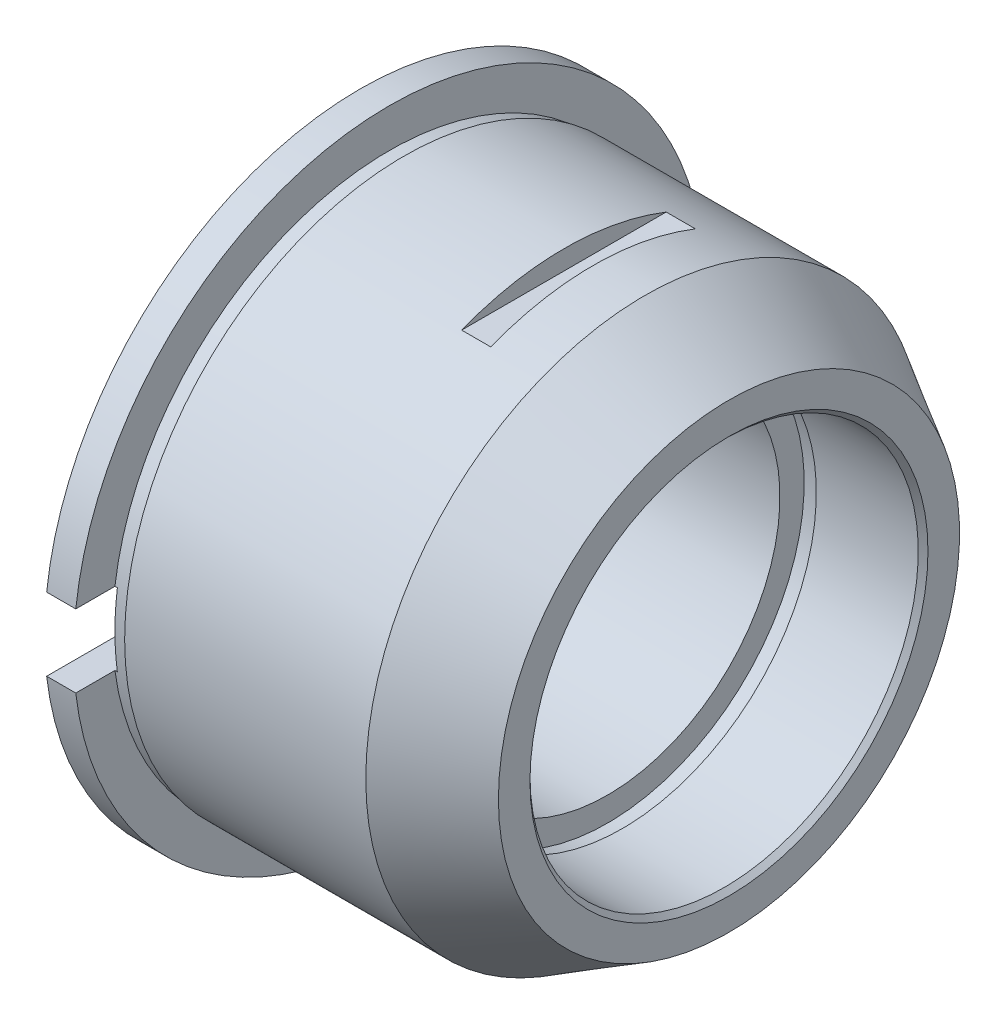
SolidWorks part; units mm, degrees
material "Сталь 20 ГОСТ 1050-88"
ref_plane "Спереди" through (0, 0, 0) normal (0, 0, 1) x (1, 0, 0)
ref_plane "Сверху" through (0, 0, 0) normal (0, 1, 0) x (1, 0, 0)
ref_plane "Справа" through (0, 0, 0) normal (1, 0, 0) x (0, 0, -1)
sketch "Эскиз1" plane through (0, 0, 0) normal (0, 0, 1) x (1, 0, 0)
  line L0 (0, 0) -> (98.5963, 0) construction
  line L1 (0, 39) -> (6, 39)
  line L2 (6, 39) -> (6, 35.5)
  line L3 (6, 35.5) -> (51, 35.5)
  line L4 (51, 35.5) -> (51, 40.5)
  line L5 (51, 40.5) -> (54, 40.5)
  line L6 (54, 40.5) -> (54, 40)
  line L7 (54, 40) -> (75, 40)
  line L8 (76, 41) -> (76, 47.5)
  line L9 (76, 47.5) -> (58.6795, 57.5)
  line L10 (58.6795, 57.5) -> (9, 57.5)
  line L11 (75, 40) -> (76, 41)
  line L15 (9, 57.5) -> (9, 57)
  line L16 (9, 57) -> (6, 57)
  line L17 (6, 57) -> (6, 65)
  line L18 (6, 65) -> (0, 65)
  line L19 (0, 65) -> (0, 39)
  point P11 (76, 40)
  dimension "D1" = 71
  dimension "D2" = 81
  dimension "D3" = 80
  dimension "D4" = 78
  dimension "D5" = 130
  dimension "D6" = 95
  dimension "D7" = 30
  dimension "D8" = 115
  dimension "D9" = 114
  dimension "D10" = 25
  dimension "D11" = 3
  dimension "D12" = 6
  dimension "D13" = 76
  dimension "D14" = 6
  dimension "D15" = 3
  dimension "D16" = 1
  dimension "D17" = 45
revolve "Повернуть1" add sketch "Эскиз1" angle 360 about L0
sketch "Эскиз2" plane through (0, 0, 0) normal (0, 0, 1) x (1, 0, 0)
  line L0 (58.6795, 57.5) -> (9, 57.5) construction
  line L1 (48, 57.5) -> (42, 57.5)
  line L2 (48, 57.5) -> (48, 53.5)
  line L3 (48, 53.5) -> (42, 53.5)
  line L4 (42, 57.5) -> (42, 53.5)
  line L5 (0, 65) -> (0, -65) construction
  line L7 (0, 7.5) -> (6.5, 7.5)
  line L8 (0, 7.5) -> (0, -7.5)
  line L9 (0, -7.5) -> (6.5, -7.5)
  line L10 (6.5, 7.5) -> (6.5, -7.5)
  dimension "D1" = 48
  dimension "D2" = 6
  dimension "D3" = 4
  dimension "D4" = 15
  dimension "D5" = 6.5
extrude "Вырез-Вытянуть1" cut sketch "Эскиз2" against normal through all and the other way through all
